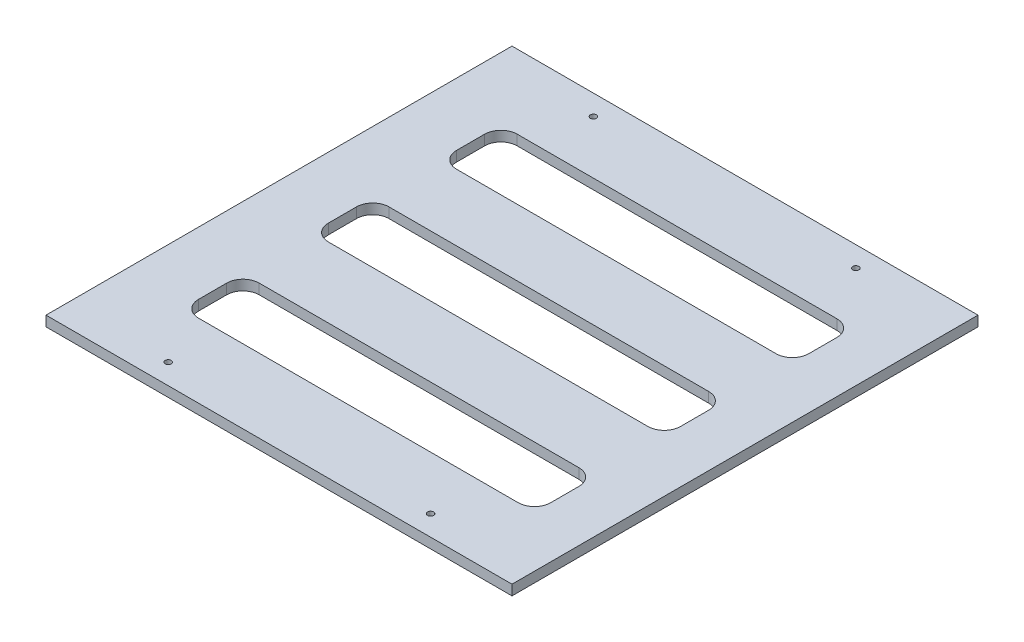
SolidWorks part; units mm, degrees
material "Acrylic (Medium-high impact)"
ref_plane "Front Plane" through (0, 0, 0) normal (0, 0, 1) x (1, 0, 0)
ref_plane "Top Plane" through (0, 0, 0) normal (0, 1, 0) x (1, 0, 0)
ref_plane "Right Plane" through (0, 0, 0) normal (1, 0, 0) x (0, 0, -1)
sketch "Sketch1" plane through (0, 0, 0) normal (0, 1, 0) x (1, 0, 0)
  line L0 (114.5, 0) -> (114.5, -229) construction
  line L1 (0, 0) -> (229, 0)
  line L2 (0, 0) -> (0, -229)
  line L3 (0, -229) -> (229, -229)
  line L4 (229, 0) -> (229, -229)
  line L5 (0, -114.5) -> (229, -114.5) construction
  circle A0 centre (179, -10) radius 1.5
  circle A1 centre (50, -10) radius 1.5
  circle A2 centre (179, -219) radius 1.5
  circle A3 centre (50, -219) radius 1.5
  dimension "D3" = 3
  dimension "D5" = 10
  dimension "D1" = 229
  dimension "D2" = 229
  dimension "D4" = 50
extrude "Boss-Extrude1" add sketch "Sketch1" along normal blind 5
sketch "Sketch2" plane through (0, 5, 0) normal (0, 1, 0) x (1, 0, 0)
  line L0 (0, -114.5) -> (229, -114.5) construction
  line L1 (38.7603, -36.198) -> (195.8327, -36.198)
  line L2 (30.7603, -44.198) -> (30.7603, -58.0273)
  line L3 (38.7603, -66.0273) -> (195.8327, -66.0273)
  line L4 (203.8327, -44.198) -> (203.8327, -58.0273)
  line L5 (0, 0) -> (0, -229) construction
  line L6 (229, -229) -> (229, 0) construction
  line L7 (229, 0) -> (0, 0) construction
  line L8 (203.8327, -184.802) -> (203.8327, -170.9727)
  line L9 (38.7603, -162.9727) -> (195.8327, -162.9727)
  line L10 (38.7603, -192.802) -> (195.8327, -192.802)
  line L11 (30.7603, -184.802) -> (30.7603, -170.9727)
  line L12 (38.22, -98.6532) -> (195.29, -98.6532)
  line L13 (30.22, -106.6532) -> (30.22, -120.4825)
  line L14 (38.22, -128.4825) -> (195.29, -128.4825)
  line L15 (203.29, -106.6532) -> (203.29, -120.4825)
  arc A0 (203.8327, -44.198) -> (195.8327, -36.198) centre (195.8327, -44.198) ccw
  arc A1 (195.8327, -66.0273) -> (203.8327, -58.0273) centre (195.8327, -58.0273) ccw
  arc A2 (30.7603, -58.0273) -> (38.7603, -66.0273) centre (38.7603, -58.0273) ccw
  arc A3 (38.7603, -36.198) -> (30.7603, -44.198) centre (38.7603, -44.198) ccw
  arc A4 (203.8327, -184.802) -> (195.8327, -192.802) centre (195.8327, -184.802) cw
  arc A5 (195.8327, -162.9727) -> (203.8327, -170.9727) centre (195.8327, -170.9727) cw
  arc A6 (30.7603, -170.9727) -> (38.7603, -162.9727) centre (38.7603, -170.9727) cw
  arc A7 (38.7603, -192.802) -> (30.7603, -184.802) centre (38.7603, -184.802) cw
  arc A8 (203.29, -106.6532) -> (195.29, -98.6532) centre (195.29, -106.6532) ccw
  arc A9 (195.29, -128.4825) -> (203.29, -120.4825) centre (195.29, -120.4825) ccw
  arc A10 (30.22, -120.4825) -> (38.22, -128.4825) centre (38.22, -120.4825) ccw
  arc A11 (38.22, -98.6532) -> (30.22, -106.6532) centre (38.22, -106.6532) ccw
  dimension "D1" = 8
  dimension "D2" = 157.0724
  dimension "D3" = 13.8293
  dimension "D4" = 25.1673
  dimension "D5" = 36.198
  dimension "D6" = 32.6259
  dimension "D7" = 25.71
  dimension "D8" = 157.07
  dimension "D9" = 34.4902
  dimension "D10" = 30.22
extrude "Cut-Extrude1" cut sketch "Sketch2" against normal blind 5
